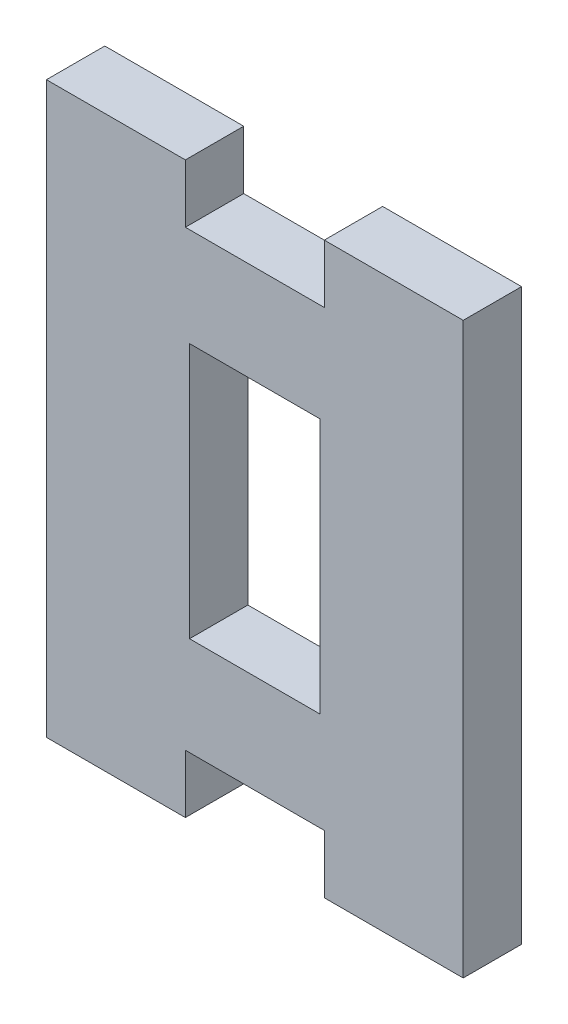
SolidWorks part; units mm, degrees
ref_plane "Front Plane" through (0, 0, 0) normal (0, 0, 1) x (1, 0, 0)
ref_plane "Top Plane" through (0, 0, 0) normal (0, 1, 0) x (1, 0, 0)
ref_plane "Right Plane" through (0, 0, 0) normal (1, 0, 0) x (0, 0, -1)
sketch "Sketch1" plane through (0, 0, 0) normal (0, 0, 1) x (1, 0, 0)
  line L1 (-14.5564, 3.9693) -> (23.5436, 3.9693)
  line L2 (-14.5564, 3.9693) -> (-14.5564, -48.1007)
  line L3 (-14.5564, -48.1007) -> (23.5436, -48.1007)
  line L4 (23.5436, 3.9693) -> (23.5436, -48.1007)
  dimension "D1" = 38.1
extrude "Boss-Extrude1" add sketch "Sketch1" along normal blind 5.334
sketch "Sketch2" plane through (0, 0, 5.334) normal (0, 0, 1) x (1, 0, 0)
  line L0 (4.4936, 3.9693) -> (4.4936, -48.1007) construction
  line L1 (23.5436, 3.9693) -> (-14.5564, 3.9693) construction
  line L2 (-14.5564, -48.1007) -> (23.5436, -48.1007) construction
  line L3 (23.5436, -22.0657) -> (-14.5564, -22.0657) construction
  line L4 (23.5436, -48.1007) -> (23.5436, 3.9693) construction
  line L5 (-14.5564, 3.9693) -> (-14.5564, -48.1007) construction
  line L7 (-1.4754, -33.7497) -> (10.4626, -33.7497)
  line L8 (-1.4754, -33.7497) -> (-1.4754, -10.3817)
  line L9 (-1.4754, -10.3817) -> (10.4626, -10.3817)
  line L10 (10.4626, -33.7497) -> (10.4626, -10.3817)
  line L11 (-1.4754, -33.7497) -> (10.4626, -10.3817) construction
  line L12 (-1.4754, -10.3817) -> (10.4626, -33.7497) construction
  point P12 (4.4936, -22.0657)
  dimension "D1" = 11.938
  dimension "D2" = 23.368
extrude "Cut-Extrude1" cut sketch "Sketch2" against normal through all
sketch "Sketch3" plane through (0, 0, 5.334) normal (0, 0, 1) x (1, 0, 0)
  line L0 (23.5436, 3.9693) -> (-14.5564, 3.9693) construction
  line L1 (-1.8564, 3.9693) -> (10.8436, 3.9693)
  line L2 (-1.8564, 3.9693) -> (-1.8564, -1.3647)
  line L3 (-1.8564, -1.3647) -> (10.8436, -1.3647)
  line L4 (10.8436, 3.9693) -> (10.8436, -1.3647)
  line L5 (-1.8564, -1.3647) -> (-14.5564, -1.3647) construction
  line L6 (-14.5564, 3.9693) -> (-14.5564, -48.1007) construction
  line L7 (10.8436, -1.3647) -> (23.5436, -1.3647) construction
  line L8 (23.5436, -48.1007) -> (23.5436, 3.9693) construction
  line L9 (-14.5564, -22.0657) -> (23.5436, -22.0657) construction
  line L10 (10.8436, -42.7667) -> (23.5436, -42.7667) construction
  line L11 (-1.8564, -42.7667) -> (-14.5564, -42.7667) construction
  line L12 (10.8436, -48.1007) -> (10.8436, -42.7667)
  line L13 (-1.8564, -42.7667) -> (10.8436, -42.7667)
  line L14 (-1.8564, -48.1007) -> (-1.8564, -42.7667)
  line L15 (-1.8564, -48.1007) -> (10.8436, -48.1007)
  dimension "D1" = 5.334
extrude "Cut-Extrude2" cut sketch "Sketch3" against normal through all
equation "\"MDF\"= .21in"
equation "\"Foamcore\"= .13in"
equation "\"Gmaterial\"= \"MDF\""
equation "\"D1@Boss-Extrude1\"=\"MDF\""
equation "\"D1@Sketch3\"=\"MDF\""
